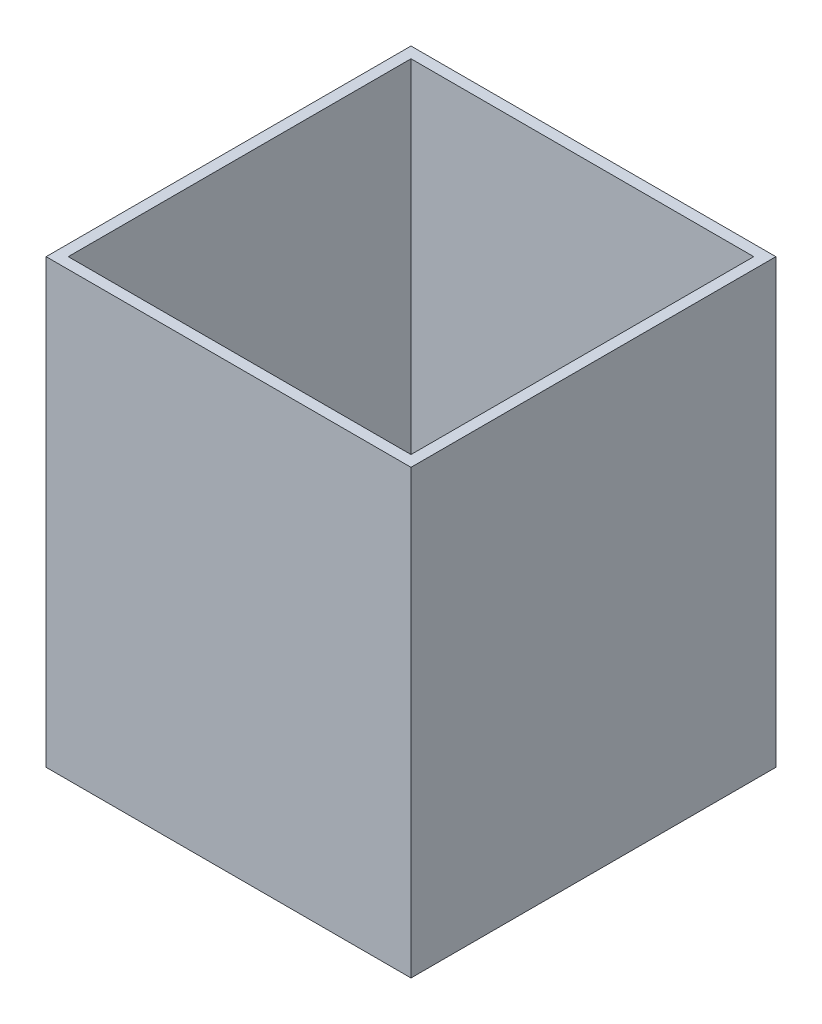
SolidWorks part; units mm, degrees
ref_plane "Front Plane" through (0, 0, 0) normal (0, 0, 1) x (1, 0, 0)
ref_plane "Top Plane" through (0, 0, 0) normal (0, 1, 0) x (1, 0, 0)
ref_plane "Right Plane" through (0, 0, 0) normal (1, 0, 0) x (0, 0, -1)
sketch "Sketch1" plane through (0, 0, 0) normal (0, 1, 0) x (1, 0, 0)
  line L0 (1, 1) -> (1, 32)
  line L1 (0, 0) -> (33, 0)
  line L2 (0, 0) -> (0, 33)
  line L3 (0, 33) -> (33, 33)
  line L4 (33, 0) -> (33, 33)
  line L5 (1, 32) -> (32, 32)
  line L6 (32, 1) -> (32, 32)
  line L7 (1, 1) -> (32, 1)
  dimension "D1" = 1
extrude "Boss-Extrude2" add sketch "Sketch1" along normal blind 40
sketch "Sketch2" plane through (0, 0, 0) normal (0, -1, 0) x (1, 0, 0)
  line L1 (32, -1) -> (1, -1)
  line L2 (32, -1) -> (32, -32)
  line L3 (32, -32) -> (1, -32)
  line L4 (1, -1) -> (1, -32)
extrude "Boss-Extrude3" add sketch "Sketch2" against normal blind 1
